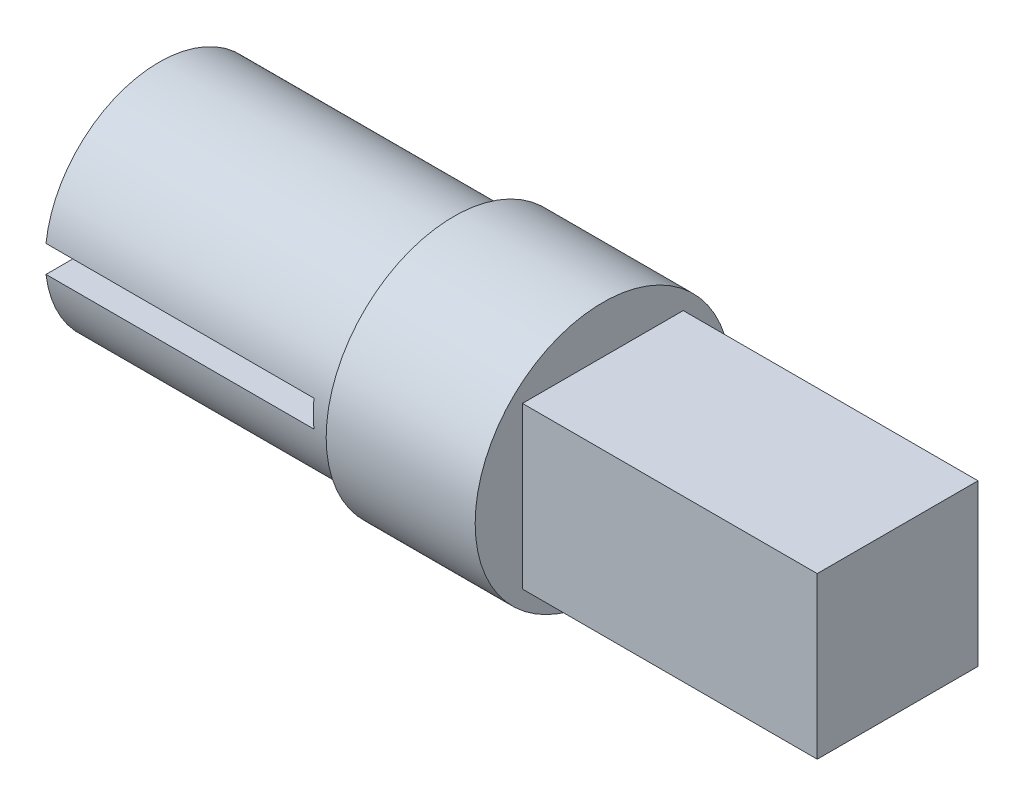
SolidWorks part; units mm, degrees
ref_plane "Front Plane" through (0, 0, 0) normal (0, 0, 1) x (1, 0, 0)
ref_plane "Top Plane" through (0, 0, 0) normal (0, 1, 0) x (1, 0, 0)
ref_plane "Right Plane" through (0, 0, 0) normal (1, 0, 0) x (0, 0, -1)
sketch "Sketch1" plane through (0, 0, 0) normal (1, 0, 0) x (0, 0, -1)
  circle A0 centre (0, 0) radius 4.765
  dimension "D1" = 9.53
extrude "Boss-Extrude1" add sketch "Sketch1" along normal mid plane 5.56
sketch "Sketch2" plane through (-2.78, 0, 0) normal (-1, 0, 0) x (0, 0, 1)
  circle A1 centre (0, 0) radius 2.85 construction
  circle A2 centre (0, 0) radius 4.25
  dimension "D1" = 5.7
  dimension "D2" = 8.5
extrude "Boss-Extrude2" add sketch "Sketch2" along normal blind 11
sketch "Sketch3" plane through (2.78, 0, 0) normal (1, 0, 0) x (0, 0, -1)
  line L1 (-3, 3) -> (3, 3)
  line L2 (-3, 3) -> (-3, -3)
  line L3 (-3, -3) -> (3, -3)
  line L4 (3, 3) -> (3, -3)
  line L5 (-3, 3) -> (3, -3) construction
  line L6 (-3, -3) -> (3, 3) construction
  point P0 (0, 0)
  dimension "D1" = 6
extrude "Boss-Extrude3" add sketch "Sketch3" along normal blind 11
sketch "Sketch4" plane through (-2.78, 0, 0) normal (-1, 0, 0) x (0, 0, 1)
  line L0 (-4.25, 0) -> (4.25, 0) construction
  circle A0 centre (0, 0) radius 4.25 construction
  circle A1 centre (0, 0) radius 4.25 construction
  circle A2 centre (0, 0) radius 2.85
  dimension "D1" = 5.7
extrude "Cut-Extrude1" cut sketch "Sketch4" against normal up to surface (11 mm away) from surface at 11 up to face at (-2.78, 0, 4.25) starting at face at (-13.78, 0, 4.25)
sketch "Sketch5" plane through (-13.78, 0, 0) normal (-1, 0, 0) x (0, 0, 1)
  line L0 (-4.765, 0) -> (4.765, 0) construction
  line L1 (-4.765, -0.5) -> (4.765, -0.5)
  line L2 (-4.765, 0.5) -> (4.765, 0.5)
  circle A0 centre (0, 0) radius 4.765 construction
  arc A1 (-4.7387, 0.5) -> (-4.7387, -0.5) centre (0, 0) ccw
  arc A2 (4.7387, 0.5) -> (-4.7387, 0.5) centre (0, 0) ccw construction
  arc A3 (-4.7387, -0.5) -> (4.7387, -0.5) centre (0, 0) ccw construction
  arc A4 (4.7387, -0.5) -> (4.7387, 0.5) centre (0, 0) ccw
  circle M2 centre (0, 0) radius 2.85
  circle M3 centre (0, 0) radius 4.25
  dimension "D1" = 0.5
  dimension "D2" = 0.5
extrude "Cut-Extrude2" cut sketch "Sketch5" against normal blind 10 contours L2 L1 M3 M2 | L2 A1 L1 M3 | L2 L1 M2 | L2 L1 M2 M3 | L1 A4 L2 M3
equation "\"ID\" = 9.53mm"
equation "\"ID_Extension\"= 11mm"
equation "\"ServoHorn\"= 5.7mm"
equation "\"CarrierLength\"= 10mm"
equation "\"D1@Sketch1\"=\"ID\""
equation "\"ID_Bearing\" = 5.56mm"
equation "\"D1@Boss-Extrude1\"=\"ID_Bearing\""
equation "\"D1@Sketch2\"=\"ServoHorn\""
equation "\"D1@Boss-Extrude2\"=\"ID_Extension\""
equation "\"D1@Sketch4\"=\"ServoHorn\""
